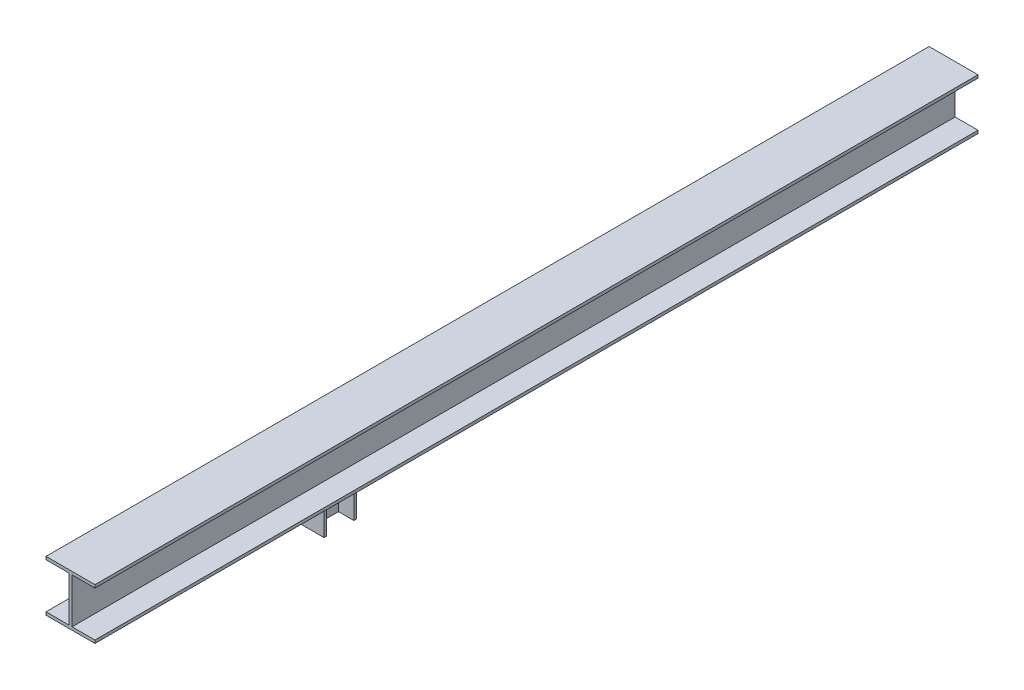
SolidWorks part; units mm, degrees
ref_plane "Front Plane" through (0, 0, 0) normal (0, 0, 1) x (1, 0, 0)
ref_plane "Top Plane" through (0, 0, 0) normal (0, 1, 0) x (1, 0, 0)
ref_plane "Right Plane" through (0, 0, 0) normal (1, 0, 0) x (0, 0, -1)
sketch "Sketch7" plane through (0, 0, 0) normal (0, 0, 1) x (1, 0, 0)
  line L0 (100.2571, 502.4219) -> (242.9071, 502.4219)
  line L1 (242.9071, 221.9219) -> (100.2571, 221.9219)
  line L2 (-61.8929, 221.9219) -> (-61.8929, 203.4219)
  line L3 (-61.8929, 203.4219) -> (242.9071, 203.4219)
  line L4 (242.9071, 203.4219) -> (242.9071, 221.9219)
  line L5 (80.7571, 221.9219) -> (-61.8929, 221.9219)
  line L6 (100.2571, 221.9219) -> (100.2571, 502.4219)
  line L8 (242.9071, 502.4219) -> (242.9071, 520.9219)
  line L9 (242.9071, 520.9219) -> (-61.8929, 520.9219)
  line L10 (-61.8929, 520.9219) -> (-61.8929, 502.4219)
  line L11 (-61.8929, 502.4219) -> (80.7571, 502.4219)
  line L12 (80.7571, 502.4219) -> (80.7571, 221.9219)
extrude "Boss-Extrude7" add sketch "Sketch7" along normal blind 5500 separate body
sketch "Sketch8" plane through (0, 203.4219, 0) normal (0, -1, 0) x (1, 0, 0)
  line L0 (-9.4929, 4020) -> (190.5071, 4020)
  line L1 (-9.4929, 4020) -> (-9.4929, 4005)
  line L2 (-9.4929, 3820) -> (-9.4929, 3835)
  line L3 (190.5071, 3820) -> (190.5071, 3835)
  line L4 (190.5071, 3820) -> (-9.4929, 3820)
  line L5 (190.5071, 4020) -> (190.5071, 4005)
  line L6 (-9.4929, 4005) -> (86.0071, 4005)
  line L7 (95.0071, 4005) -> (190.5071, 4005)
  line L8 (190.5071, 3835) -> (95.0071, 3835)
  line L9 (86.0071, 3835) -> (86.0071, 4005)
  line L10 (95.0071, 3835) -> (95.0071, 4005)
  line L11 (86.0071, 3835) -> (-9.4929, 3835)
  line L13 (201.1964, 3234.5127) -> (-58.8036, 3234.5127) construction
  line L14 (-61.8929, 0) -> (242.9071, 0) construction
  line L15 (-61.8929, 3920) -> (-83.616, 3971.1101) construction
  line L16 (-61.8929, 3920) -> (242.9071, 3920) construction
  line L17 (90.5071, 3920) -> (90.5071, 3939.4309) construction
  line L18 (-61.8929, 5500) -> (-61.8929, 0) construction
  line L19 (242.9071, 3920) -> (315.5904, 3977.4064) construction
  line L20 (114.3177, 3920) -> (155.9563, 3868.9684) construction
  line L22 (242.9071, 5500) -> (242.9071, 0) construction
  dimension "D1" = 3820
  dimension "D3" = 200
  dimension "D4" = 200
  dimension "D5" = 15
  dimension "D6" = 15
  dimension "D7" = 15
  dimension "D8" = 15
extrude "Boss-Extrude8" add sketch "Sketch8" along normal blind 195.5 separate body
sketch "Sketch9" plane through (0, 203.4219, 0) normal (0, -1, 0) x (1, 0, 0)
  line L0 (-61.8929, 5500) -> (-61.8929, 0) construction
  line L1 (-61.8929, 5465.9142) -> (-182.146, 5628.9118)
  line L2 (-182.146, 5628.9118) -> (103.3648, 5740.9118)
  line L3 (103.3648, 5740.9118) -> (446.7563, 5731.5253)
  line L4 (446.7563, 5731.5253) -> (446.7563, 5340.4578)
  line L5 (446.7563, 5340.4578) -> (295.8402, 5216.2744)
  spline S0 degree 3 poles (-61.8929, 5465.9142) (166.8091, 5514.4944) (109.9985, 5223.499) (295.8402, 5216.2744) knots 0 0 0 0 1 1 1 1
